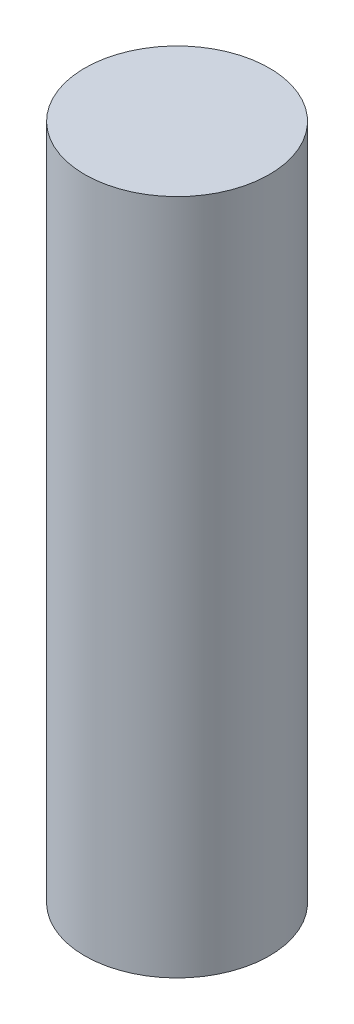
SolidWorks part; units mm, degrees
ref_plane "Front Plane" through (0, 0, 0) normal (0, 0, 1) x (1, 0, 0)
ref_plane "Top Plane" through (0, 0, 0) normal (0, 1, 0) x (1, 0, 0)
ref_plane "Right Plane" through (0, 0, 0) normal (1, 0, 0) x (0, 0, -1)
sketch "Sketch1" plane through (0, 0, 0) normal (0, 1, 0) x (1, 0, 0)
  circle A0 centre (0, 0) radius 1.5
  dimension "D1" = 3
extrude "Boss-Extrude1" add sketch "Sketch1" along normal blind 11
